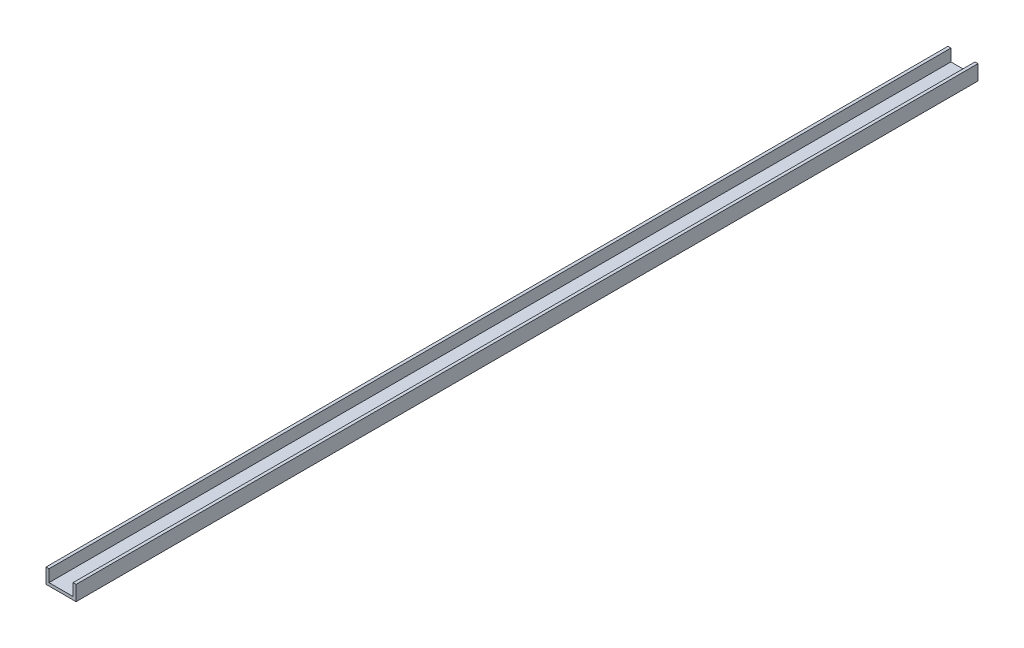
SolidWorks part; units mm, degrees
ref_plane "前视基准面" through (0, 0, 0) normal (0, 0, 1) x (1, 0, 0)
ref_plane "上视基准面" through (0, 0, 0) normal (0, 1, 0) x (1, 0, 0)
ref_plane "右视基准面" through (0, 0, 0) normal (1, 0, 0) x (0, 0, -1)
sketch "草图1" plane through (0, 0, 0) normal (0, 0, 1) x (1, 0, 0)
  line L0 (0, 0) -> (0, -5)
  line L1 (0, -5) -> (10, -5)
  line L2 (10, -5) -> (10, 0)
  line L3 (10, 0) -> (9, 0)
  line L4 (9, 0) -> (9, -4)
  line L5 (9, -4) -> (1, -4)
  line L6 (1, -4) -> (1, 0)
  line L7 (1, 0) -> (0, 0)
  line L8 (5, -4) -> (5, -5) construction
  dimension "D1" = 5
  dimension "D2" = 10
  dimension "D3" = 1
  dimension "D4" = 1
extrude "凸台-拉伸1" add sketch "草图1" along normal blind 300
